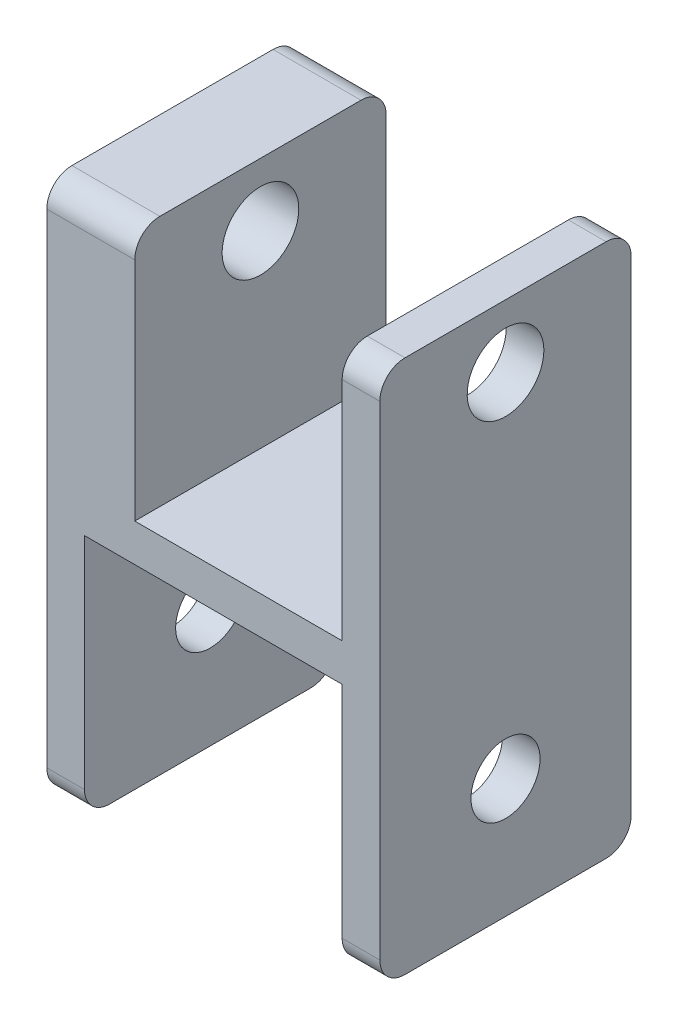
SolidWorks part; units mm, degrees
ref_plane "Front" through (0, 0, 0) normal (0, 0, 1) x (1, 0, 0)
ref_plane "Top" through (0, 0, 0) normal (0, 1, 0) x (1, 0, 0)
ref_plane "Right" through (0, 0, 0) normal (1, 0, 0) x (0, 0, -1)
sketch "Sketch1" plane through (0, 0, 0) normal (0, 0, 1) x (1, 0, 0)
  line L0 (-10.25, 1.5) -> (10.25, 1.5)
  line L1 (-13.25, 21.5) -> (-10.25, 21.5)
  line L2 (-13.25, 21.5) -> (-13.25, -21)
  line L3 (-13.25, -21) -> (-10.25, -21)
  line L4 (-10.25, 21.5) -> (-10.25, 1.5)
  line L5 (-10.25, -1.5) -> (-10.25, -21)
  line L7 (-10.25, -1.5) -> (10.25, -1.5)
  line L8 (10.25, 21.5) -> (10.25, 1.5)
  line L9 (10.25, 21.5) -> (13.25, 21.5)
  line L11 (10.25, -21) -> (13.25, -21)
  line L12 (13.25, 21.5) -> (13.25, -21)
  line L13 (10.25, -1.5) -> (10.25, -21)
  line L14 (0, 1.5) -> (0, -1.5) construction
  point P14 (0, 0)
  dimension "D1" = 20.5
  dimension "D2" = 3
  dimension "D3" = 19.5
  dimension "D4" = 20
  dimension "D5" = 3
extrude "Boss-Extrude1" add sketch "Sketch1" along normal blind 20
sketch "Sketch2" plane through (13.25, 0, 0) normal (1, 0, 0) x (0, 0, -1)
  line L0 (-20, -21) -> (-20, -11.5) construction
  line L1 (-20, -21) -> (-20, 21.5) construction
  line L2 (-20, -11.5) -> (-10, -11.5) construction
  line L3 (-10, -11.5) -> (0, -11.5) construction
  line L4 (0, -21) -> (0, 21.5) construction
  line L5 (-20, 21.5) -> (0, 21.5) construction
  line L6 (-20, -1.5) -> (0, -1.5) construction
  circle A0 centre (-10, -11.5) radius 2.75
  circle A1 centre (-10, 16.5) radius 3.05
  dimension "D2" = 5.5
  dimension "D3" = 6.1
  dimension "D1" = 10
  dimension "D4" = 5
extrude "Cut-Extrude1" cut sketch "Sketch2" against normal through all
sketch "Sketch3" plane through (-10.25, 0, 0) normal (1, 0, 0) x (0, 0, -1)
  line L0 (0, 1.5) -> (0, 21.5) construction
  line L1 (-20, 21.5) -> (0, 21.5) construction
  line L2 (-20, 1.5) -> (-20, 21.5) construction
  line L4 (0, 1.5) -> (0, 21.5)
  line L5 (-20, 21.5) -> (0, 21.5)
  line L6 (-20, 1.5) -> (-20, 21.5)
  line L7 (0, 1.5) -> (-20, 1.5)
  circle A0 centre (-10, 16.5) radius 3.05 construction
  circle A1 centre (-10, 16.5) radius 3.05
extrude "Boss-Extrude2" add sketch "Sketch3" along normal blind 4
fillet "Fillet1" radius 2 8 edges at (11.75, 21.5, 0) (11.75, 21.5, 20) (-9.75, 21.5, 0) (-9.75, 21.5, 20) (11.75, -21, 0) (-11.75, -21, 0) (-11.75, -21, 20) (11.75, -21, 20)
